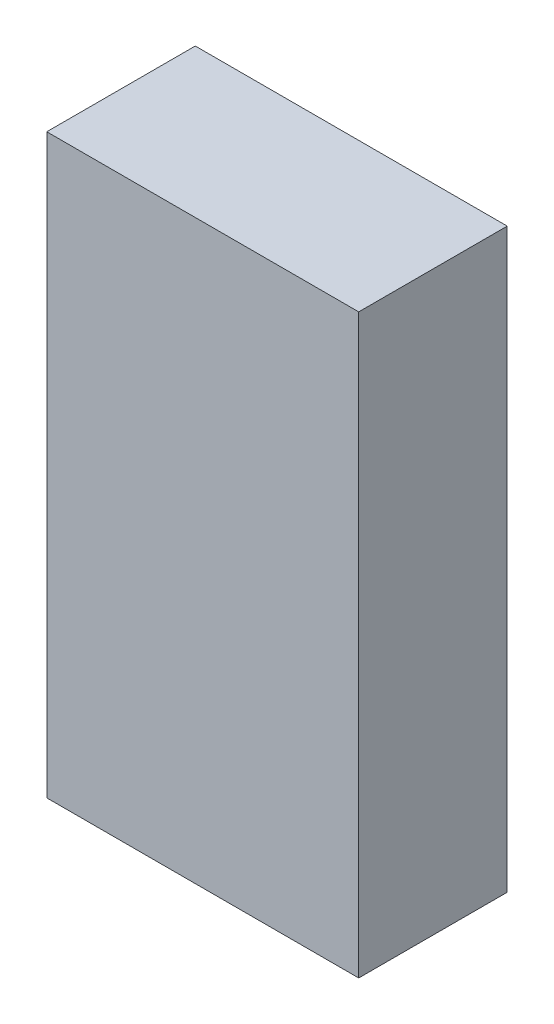
SolidWorks part; units mm, degrees
ref_plane "Alzado" through (0, 0, 0) normal (0, 0, 1) x (1, 0, 0)
ref_plane "Planta" through (0, 0, 0) normal (0, 1, 0) x (1, 0, 0)
ref_plane "Vista lateral" through (0, 0, 0) normal (1, 0, 0) x (0, 0, -1)
sketch "Croquis1" plane through (0, 0, 0) normal (0, 1, 0) x (1, 0, 0)
  line L1 (-691.2725, 308.5222) -> (33.8593, 308.5222)
  line L2 (-691.2725, 308.5222) -> (-691.2725, -36.6991)
  line L3 (-691.2725, -36.6991) -> (33.8593, -36.6991)
  line L4 (33.8593, 308.5222) -> (33.8593, -36.6991)
  line L5 (-691.2725, 308.5222) -> (33.8593, -36.6991) construction
  line L6 (-691.2725, -36.6991) -> (33.8593, 308.5222) construction
  point P0 (-328.7066, 135.9115)
extrude "Saliente-Extruir1" add sketch "Croquis1" along normal blind 1341
